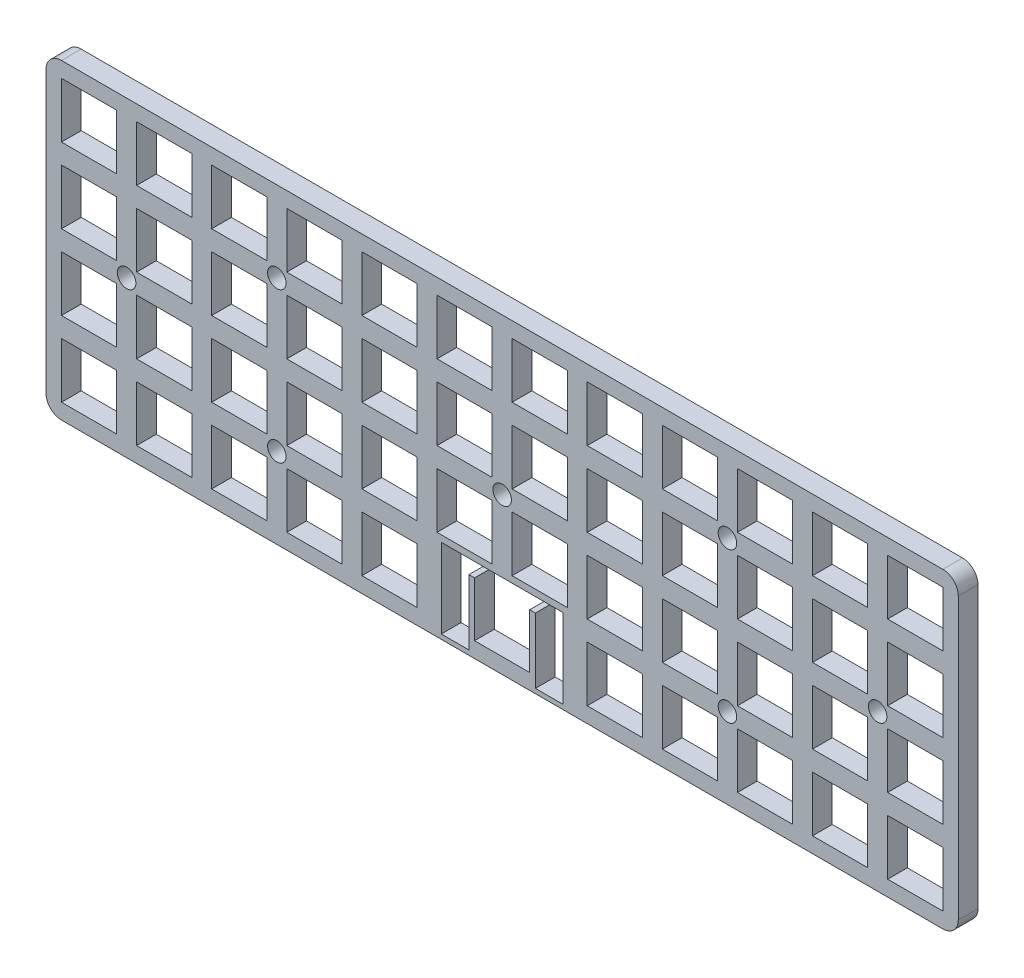
SolidWorks part; units mm, degrees
ref_plane "Alzado" through (0, 0, 0) normal (0, 0, 1) x (1, 0, 0)
ref_plane "Planta" through (0, 0, 0) normal (0, 1, 0) x (1, 0, 0)
ref_plane "Vista lateral" through (0, 0, 0) normal (1, 0, 0) x (0, 0, -1)
sketch "Reference" plane through (0, 0, 0) normal (0, 0, 1) x (1, 0, 0)
  line L0 (10.05, 76.2) -> (10.05, 83.2)
  line L1 (12.05, 85.2) -> (235.6, 85.2)
  line L2 (237.6, 83.2) -> (237.6, 12.05)
  line L3 (10.05, 12.05) -> (10.05, 76.2)
  line L4 (235.6, 10.05) -> (12.05, 10.05)
  line L5 (47.625, 85.2) -> (47.625, 87.2)
  line L6 (52.625, 87.2) -> (42.625, 87.2)
  line L7 (42.625, 87.2) -> (42.625, 85.2)
  line L8 (52.625, 87.2) -> (52.625, 85.2)
  line L9 (47.625, 87.2) -> (47.625, 89.2)
  line L10 (12.05, 69.2) -> (26.05, 69.2)
  line L11 (26.05, 83.2) -> (12.05, 83.2)
  line L12 (26.05, 69.2) -> (26.05, 83.2)
  line L13 (12.05, 83.2) -> (12.05, 69.2)
  line L14 (31.1, 69.2) -> (45.1, 69.2)
  line L15 (45.1, 83.2) -> (31.1, 83.2)
  line L16 (45.1, 69.2) -> (45.1, 83.2)
  line L17 (31.1, 83.2) -> (31.1, 69.2)
  line L18 (50.15, 69.2) -> (64.15, 69.2)
  line L19 (64.15, 83.2) -> (50.15, 83.2)
  line L20 (64.15, 69.2) -> (64.15, 83.2)
  line L21 (50.15, 83.2) -> (50.15, 69.2)
  line L22 (69.2, 69.2) -> (83.2, 69.2)
  line L23 (83.2, 83.2) -> (69.2, 83.2)
  line L24 (83.2, 69.2) -> (83.2, 83.2)
  line L25 (69.2, 83.2) -> (69.2, 69.2)
  line L26 (88.25, 69.2) -> (102.25, 69.2)
  line L27 (102.25, 83.2) -> (88.25, 83.2)
  line L28 (102.25, 69.2) -> (102.25, 83.2)
  line L29 (88.25, 83.2) -> (88.25, 69.2)
  line L30 (107.3, 69.2) -> (121.3, 69.2)
  line L31 (121.3, 83.2) -> (107.3, 83.2)
  line L32 (121.3, 69.2) -> (121.3, 83.2)
  line L33 (107.3, 83.2) -> (107.3, 69.2)
  line L34 (126.35, 69.2) -> (140.35, 69.2)
  line L35 (140.35, 83.2) -> (126.35, 83.2)
  line L36 (140.35, 69.2) -> (140.35, 83.2)
  line L37 (126.35, 83.2) -> (126.35, 69.2)
  line L38 (145.4, 69.2) -> (159.4, 69.2)
  line L39 (159.4, 83.2) -> (145.4, 83.2)
  line L40 (159.4, 69.2) -> (159.4, 83.2)
  line L41 (145.4, 83.2) -> (145.4, 69.2)
  line L42 (164.45, 69.2) -> (178.45, 69.2)
  line L43 (178.45, 83.2) -> (164.45, 83.2)
  line L44 (178.45, 69.2) -> (178.45, 83.2)
  line L45 (164.45, 83.2) -> (164.45, 69.2)
  line L46 (183.5, 69.2) -> (197.5, 69.2)
  line L47 (197.5, 83.2) -> (183.5, 83.2)
  line L48 (197.5, 69.2) -> (197.5, 83.2)
  line L49 (183.5, 83.2) -> (183.5, 69.2)
  line L50 (202.55, 69.2) -> (216.55, 69.2)
  line L51 (216.55, 83.2) -> (202.55, 83.2)
  line L52 (216.55, 69.2) -> (216.55, 83.2)
  line L53 (202.55, 83.2) -> (202.55, 69.2)
  line L54 (221.6, 69.2) -> (235.6, 69.2)
  line L55 (235.6, 83.2) -> (221.6, 83.2)
  line L56 (235.6, 69.2) -> (235.6, 83.2)
  line L57 (221.6, 83.2) -> (221.6, 69.2)
  line L58 (12.05, 50.15) -> (26.05, 50.15)
  line L59 (26.05, 64.15) -> (12.05, 64.15)
  line L60 (26.05, 50.15) -> (26.05, 64.15)
  line L61 (12.05, 64.15) -> (12.05, 50.15)
  line L62 (31.1, 50.15) -> (45.1, 50.15)
  line L63 (45.1, 64.15) -> (31.1, 64.15)
  line L64 (45.1, 50.15) -> (45.1, 64.15)
  line L65 (31.1, 64.15) -> (31.1, 50.15)
  line L66 (50.15, 50.15) -> (64.15, 50.15)
  line L67 (64.15, 64.15) -> (50.15, 64.15)
  line L68 (64.15, 50.15) -> (64.15, 64.15)
  line L69 (50.15, 64.15) -> (50.15, 50.15)
  line L70 (69.2, 50.15) -> (83.2, 50.15)
  line L71 (83.2, 64.15) -> (69.2, 64.15)
  line L72 (83.2, 50.15) -> (83.2, 64.15)
  line L73 (69.2, 64.15) -> (69.2, 50.15)
  line L74 (88.25, 50.15) -> (102.25, 50.15)
  line L75 (102.25, 64.15) -> (88.25, 64.15)
  line L76 (102.25, 50.15) -> (102.25, 64.15)
  line L77 (88.25, 64.15) -> (88.25, 50.15)
  line L78 (107.3, 50.15) -> (121.3, 50.15)
  line L79 (121.3, 64.15) -> (107.3, 64.15)
  line L80 (121.3, 50.15) -> (121.3, 64.15)
  line L81 (107.3, 64.15) -> (107.3, 50.15)
  line L82 (126.35, 50.15) -> (140.35, 50.15)
  line L83 (140.35, 64.15) -> (126.35, 64.15)
  line L84 (140.35, 50.15) -> (140.35, 64.15)
  line L85 (126.35, 64.15) -> (126.35, 50.15)
  line L86 (145.4, 50.15) -> (159.4, 50.15)
  line L87 (159.4, 64.15) -> (145.4, 64.15)
  line L88 (159.4, 50.15) -> (159.4, 64.15)
  line L89 (145.4, 64.15) -> (145.4, 50.15)
  line L90 (164.45, 50.15) -> (178.45, 50.15)
  line L91 (178.45, 64.15) -> (164.45, 64.15)
  line L92 (178.45, 50.15) -> (178.45, 64.15)
  line L93 (164.45, 64.15) -> (164.45, 50.15)
  line L94 (183.5, 50.15) -> (197.5, 50.15)
  line L95 (197.5, 64.15) -> (183.5, 64.15)
  line L96 (197.5, 50.15) -> (197.5, 64.15)
  line L97 (183.5, 64.15) -> (183.5, 50.15)
  line L98 (202.55, 50.15) -> (216.55, 50.15)
  line L99 (216.55, 64.15) -> (202.55, 64.15)
  line L100 (216.55, 50.15) -> (216.55, 64.15)
  line L101 (202.55, 64.15) -> (202.55, 50.15)
  line L102 (221.6, 50.15) -> (235.6, 50.15)
  line L103 (235.6, 64.15) -> (221.6, 64.15)
  line L104 (235.6, 50.15) -> (235.6, 64.15)
  line L105 (221.6, 64.15) -> (221.6, 50.15)
  line L106 (12.05, 31.1) -> (26.05, 31.1)
  line L107 (26.05, 45.1) -> (12.05, 45.1)
  line L108 (26.05, 31.1) -> (26.05, 45.1)
  line L109 (12.05, 45.1) -> (12.05, 31.1)
  line L110 (31.1, 31.1) -> (45.1, 31.1)
  line L111 (45.1, 45.1) -> (31.1, 45.1)
  line L112 (45.1, 31.1) -> (45.1, 45.1)
  line L113 (31.1, 45.1) -> (31.1, 31.1)
  line L114 (50.15, 31.1) -> (64.15, 31.1)
  line L115 (64.15, 45.1) -> (50.15, 45.1)
  line L116 (64.15, 31.1) -> (64.15, 45.1)
  line L117 (50.15, 45.1) -> (50.15, 31.1)
  line L118 (69.2, 31.1) -> (83.2, 31.1)
  line L119 (83.2, 45.1) -> (69.2, 45.1)
  line L120 (83.2, 31.1) -> (83.2, 45.1)
  line L121 (69.2, 45.1) -> (69.2, 31.1)
  line L122 (88.25, 31.1) -> (102.25, 31.1)
  line L123 (102.25, 45.1) -> (88.25, 45.1)
  line L124 (102.25, 31.1) -> (102.25, 45.1)
  line L125 (88.25, 45.1) -> (88.25, 31.1)
  line L126 (107.3, 31.1) -> (121.3, 31.1)
  line L127 (121.3, 45.1) -> (107.3, 45.1)
  line L128 (121.3, 31.1) -> (121.3, 45.1)
  line L129 (107.3, 45.1) -> (107.3, 31.1)
  line L130 (126.35, 31.1) -> (140.35, 31.1)
  line L131 (140.35, 45.1) -> (126.35, 45.1)
  line L132 (140.35, 31.1) -> (140.35, 45.1)
  line L133 (126.35, 45.1) -> (126.35, 31.1)
  line L134 (145.4, 31.1) -> (159.4, 31.1)
  line L135 (159.4, 45.1) -> (145.4, 45.1)
  line L136 (159.4, 31.1) -> (159.4, 45.1)
  line L137 (145.4, 45.1) -> (145.4, 31.1)
  line L138 (164.45, 31.1) -> (178.45, 31.1)
  line L139 (178.45, 45.1) -> (164.45, 45.1)
  line L140 (178.45, 31.1) -> (178.45, 45.1)
  line L141 (164.45, 45.1) -> (164.45, 31.1)
  line L142 (183.5, 31.1) -> (197.5, 31.1)
  line L143 (197.5, 45.1) -> (183.5, 45.1)
  line L144 (197.5, 31.1) -> (197.5, 45.1)
  line L145 (183.5, 45.1) -> (183.5, 31.1)
  line L146 (202.55, 31.1) -> (216.55, 31.1)
  line L147 (216.55, 45.1) -> (202.55, 45.1)
  line L148 (216.55, 31.1) -> (216.55, 45.1)
  line L149 (202.55, 45.1) -> (202.55, 31.1)
  line L150 (221.6, 31.1) -> (235.6, 31.1)
  line L151 (235.6, 45.1) -> (221.6, 45.1)
  line L152 (235.6, 31.1) -> (235.6, 45.1)
  line L153 (221.6, 45.1) -> (221.6, 31.1)
  line L154 (12.05, 12.05) -> (26.05, 12.05)
  line L155 (26.05, 26.05) -> (12.05, 26.05)
  line L156 (26.05, 12.05) -> (26.05, 26.05)
  line L157 (12.05, 26.05) -> (12.05, 12.05)
  line L158 (31.1, 12.05) -> (45.1, 12.05)
  line L159 (45.1, 26.05) -> (31.1, 26.05)
  line L160 (45.1, 12.05) -> (45.1, 26.05)
  line L161 (31.1, 26.05) -> (31.1, 12.05)
  line L162 (50.15, 12.05) -> (64.15, 12.05)
  line L163 (64.15, 26.05) -> (50.15, 26.05)
  line L164 (64.15, 12.05) -> (64.15, 26.05)
  line L165 (50.15, 26.05) -> (50.15, 12.05)
  line L166 (69.2, 12.05) -> (83.2, 12.05)
  line L167 (83.2, 26.05) -> (69.2, 26.05)
  line L168 (83.2, 12.05) -> (83.2, 26.05)
  line L169 (69.2, 26.05) -> (69.2, 12.05)
  line L170 (88.25, 12.05) -> (102.25, 12.05)
  line L171 (102.25, 26.05) -> (88.25, 26.05)
  line L172 (102.25, 12.05) -> (102.25, 26.05)
  line L173 (88.25, 26.05) -> (88.25, 12.05)
  line L174 (145.4, 12.05) -> (159.4, 12.05)
  line L175 (159.4, 26.05) -> (145.4, 26.05)
  line L176 (159.4, 12.05) -> (159.4, 26.05)
  line L177 (145.4, 26.05) -> (145.4, 12.05)
  line L178 (164.45, 12.05) -> (178.45, 12.05)
  line L179 (178.45, 26.05) -> (164.45, 26.05)
  line L180 (178.45, 12.05) -> (178.45, 26.05)
  line L181 (164.45, 26.05) -> (164.45, 12.05)
  line L182 (183.5, 12.05) -> (197.5, 12.05)
  line L183 (197.5, 26.05) -> (183.5, 26.05)
  line L184 (197.5, 12.05) -> (197.5, 26.05)
  line L185 (183.5, 26.05) -> (183.5, 12.05)
  line L186 (202.55, 12.05) -> (216.55, 12.05)
  line L187 (216.55, 26.05) -> (202.55, 26.05)
  line L188 (216.55, 12.05) -> (216.55, 26.05)
  line L189 (202.55, 26.05) -> (202.55, 12.05)
  line L190 (221.6, 12.05) -> (235.6, 12.05)
  line L191 (235.6, 26.05) -> (221.6, 26.05)
  line L192 (235.6, 12.05) -> (235.6, 26.05)
  line L193 (221.6, 26.05) -> (221.6, 12.05)
  line L194 (121.3, 31.1) -> (126.35, 31.1)
  line L195 (130.825, 26.05) -> (116.825, 26.05)
  line L196 (116.825, 12.05) -> (130.825, 12.05)
  line L197 (116.825, 26.05) -> (116.825, 12.05)
  line L198 (130.825, 12.05) -> (130.825, 26.05)
  line L199 (139.263, 27.05) -> (132.263, 27.05)
  line L200 (132.263, 12.05) -> (139.263, 12.05)
  line L201 (132.263, 27.05) -> (132.263, 12.05)
  line L202 (139.263, 12.05) -> (139.263, 27.05)
  line L203 (115.387, 27.05) -> (108.387, 27.05)
  line L204 (108.387, 12.05) -> (115.387, 12.05)
  line L205 (108.387, 27.05) -> (108.387, 12.05)
  line L206 (115.387, 12.05) -> (115.387, 27.05)
  line L207 (139.263, 28.05) -> (132.263, 28.05)
  line L208 (115.387, 28.05) -> (108.387, 28.05)
  line L209 (115.387, 28.05) -> (115.387, 27.05)
  line L210 (108.387, 28.05) -> (108.387, 27.05)
  line L211 (132.263, 28.05) -> (132.263, 27.05)
  line L212 (139.263, 28.05) -> (139.263, 27.05)
  line L213 (139.263, 29.45) -> (135.763, 29.45)
  line L214 (135.763, 29.45) -> (132.263, 29.45)
  line L215 (132.263, 9.3) -> (139.263, 9.3)
  line L216 (115.387, 29.45) -> (111.887, 29.45)
  line L217 (111.887, 29.45) -> (108.387, 29.45)
  line L218 (108.387, 9.3) -> (115.387, 9.3)
  line L219 (132.263, 29.45) -> (115.387, 29.45)
  line L220 (115.387, 25.85) -> (116.825, 25.85)
  line L221 (130.825, 25.85) -> (132.263, 25.85)
  line L222 (132.263, 9.3) -> (132.263, 12.05)
  line L223 (139.263, 9.3) -> (139.263, 12.05)
  line L224 (115.387, 9.3) -> (115.387, 12.05)
  line L225 (108.387, 9.3) -> (108.387, 12.05)
  line L226 (108.387, 29.45) -> (108.387, 28.05)
  line L227 (139.263, 29.45) -> (139.263, 28.05)
  circle A0 centre (19.05, 76.2) radius 2
  arc A1 (12.05, 85.2) -> (10.05, 83.2) centre (12.05, 83.2) ccw
  arc A2 (237.6, 83.2) -> (235.6, 85.2) centre (235.6, 83.2) ccw
  arc A3 (235.6, 10.05) -> (237.6, 12.05) centre (235.6, 12.05) ccw
  arc A4 (10.05, 12.05) -> (12.05, 10.05) centre (12.05, 12.05) ccw
  circle A5 centre (111.887, 27.305) radius 2
  circle A6 centre (111.887, 12.065) radius 1.524
  circle A7 centre (135.763, 12.065) radius 1.524
  circle A8 centre (135.763, 27.305) radius 2
  circle A9 centre (38.1, 76.2) radius 2
  circle A10 centre (57.15, 76.2) radius 2
  circle A11 centre (76.2, 76.2) radius 2
  circle A12 centre (95.25, 76.2) radius 2
  circle A13 centre (114.3, 76.2) radius 2
  circle A14 centre (133.35, 76.2) radius 2
  circle A15 centre (152.4, 76.2) radius 2
  circle A16 centre (171.45, 76.2) radius 2
  circle A17 centre (190.5, 76.2) radius 2
  circle A18 centre (209.55, 76.2) radius 2
  circle A19 centre (228.6, 76.2) radius 2
  circle A20 centre (19.05, 57.15) radius 2
  circle A21 centre (38.1, 57.15) radius 2
  circle A22 centre (57.15, 57.15) radius 2
  circle A23 centre (76.2, 57.15) radius 2
  circle A24 centre (95.25, 57.15) radius 2
  circle A25 centre (114.3, 57.15) radius 2
  circle A26 centre (133.35, 57.15) radius 2
  circle A27 centre (152.4, 57.15) radius 2
  circle A28 centre (171.45, 57.15) radius 2
  circle A29 centre (190.5, 57.15) radius 2
  circle A30 centre (209.55, 57.15) radius 2
  circle A31 centre (228.6, 57.15) radius 2
  circle A32 centre (19.05, 38.1) radius 2
  circle A33 centre (38.1, 38.1) radius 2
  circle A34 centre (57.15, 38.1) radius 2
  circle A35 centre (76.2, 38.1) radius 2
  circle A36 centre (95.25, 38.1) radius 2
  circle A37 centre (114.3, 38.1) radius 2
  circle A38 centre (133.35, 38.1) radius 2
  circle A39 centre (152.4, 38.1) radius 2
  circle A40 centre (171.45, 38.1) radius 2
  circle A41 centre (190.5, 38.1) radius 2
  circle A42 centre (209.55, 38.1) radius 2
  circle A43 centre (228.6, 38.1) radius 2
  circle A44 centre (19.05, 19.05) radius 2
  circle A45 centre (38.1, 19.05) radius 2
  circle A46 centre (57.15, 19.05) radius 2
  circle A47 centre (76.2, 19.05) radius 2
  circle A48 centre (95.25, 19.05) radius 2
  circle A49 centre (152.4, 19.05) radius 2
  circle A50 centre (171.45, 19.05) radius 2
  circle A51 centre (190.5, 19.05) radius 2
  circle A52 centre (209.55, 19.05) radius 2
  circle A53 centre (228.6, 19.05) radius 2
  circle A54 centre (28.575, 47.625) radius 1.35
  circle A55 centre (66.675, 66.675) radius 1.35
  circle A56 centre (66.675, 28.575) radius 1.35
  circle A57 centre (123.825, 47.625) radius 1.35
  circle A58 centre (180.975, 66.675) radius 1.35
  circle A59 centre (180.975, 28.575) radius 1.35
  circle A60 centre (219.075, 47.625) radius 1.35
  circle A61 centre (123.825, 19.05) radius 2
sketch "Croquis3" plane through (0, 0, 0) normal (0, 0, 1) x (1, 0, 0)
  line L0 (12.05, 85.2) -> (235.6, 85.2) construction
  line L1 (12.05, 10.05) -> (235.6, 10.05) construction
  line L2 (10.05, 12.05) -> (10.05, 83.2) construction
  line L3 (12.05, 85.2) -> (42.625, 85.2) construction
  line L4 (237.6, 12.05) -> (237.6, 83.2) construction
  line L5 (10.05, 12.05) -> (10.05, 76.2) construction
  line L6 (237.6, 83.2) -> (237.6, 12.05) construction
  line L7 (235.6, 10.05) -> (12.05, 10.05) construction
  line L8 (42.625, 85.2) -> (42.625, 87.2) construction
  line L9 (42.625, 87.2) -> (52.625, 87.2) construction
  line L10 (52.625, 87.2) -> (52.625, 85.2) construction
  line L11 (52.625, 85.2) -> (235.6, 85.2) construction
  line L12 (31.1, 69.2) -> (31.1, 83.2)
  line L13 (12.05, 69.2) -> (26.05, 69.2)
  line L14 (12.05, 69.2) -> (12.05, 83.2)
  line L15 (12.05, 83.2) -> (26.05, 83.2)
  line L16 (26.05, 69.2) -> (26.05, 83.2)
  line L17 (31.1, 69.2) -> (45.1, 69.2)
  line L18 (45.1, 69.2) -> (45.1, 83.2)
  line L19 (31.1, 83.2) -> (45.1, 83.2)
  line L20 (50.15, 69.2) -> (50.15, 83.2)
  line L21 (50.15, 69.2) -> (64.15, 69.2)
  line L22 (64.15, 69.2) -> (64.15, 83.2)
  line L23 (50.15, 83.2) -> (64.15, 83.2)
  line L24 (69.2, 69.2) -> (69.2, 83.2)
  line L25 (69.2, 69.2) -> (83.2, 69.2)
  line L26 (83.2, 69.2) -> (83.2, 83.2)
  line L27 (69.2, 83.2) -> (83.2, 83.2)
  line L28 (88.25, 69.2) -> (88.25, 83.2)
  line L29 (88.25, 69.2) -> (102.25, 69.2)
  line L30 (102.25, 69.2) -> (102.25, 83.2)
  line L31 (88.25, 83.2) -> (102.25, 83.2)
  line L32 (107.3, 69.2) -> (107.3, 83.2)
  line L33 (107.3, 69.2) -> (121.3, 69.2)
  line L34 (121.3, 69.2) -> (121.3, 83.2)
  line L35 (107.3, 83.2) -> (121.3, 83.2)
  line L36 (126.35, 69.2) -> (126.35, 83.2)
  line L37 (126.35, 69.2) -> (140.35, 69.2)
  line L38 (140.35, 69.2) -> (140.35, 83.2)
  line L39 (126.35, 83.2) -> (140.35, 83.2)
  line L40 (145.4, 69.2) -> (145.4, 83.2)
  line L41 (145.4, 69.2) -> (159.4, 69.2)
  line L42 (159.4, 69.2) -> (159.4, 83.2)
  line L43 (145.4, 83.2) -> (159.4, 83.2)
  line L44 (164.45, 69.2) -> (164.45, 83.2)
  line L45 (164.45, 69.2) -> (178.45, 69.2)
  line L46 (178.45, 69.2) -> (178.45, 83.2)
  line L47 (164.45, 83.2) -> (178.45, 83.2)
  line L48 (183.5, 69.2) -> (183.5, 83.2)
  line L49 (183.5, 69.2) -> (197.5, 69.2)
  line L50 (197.5, 69.2) -> (197.5, 83.2)
  line L51 (183.5, 83.2) -> (197.5, 83.2)
  line L52 (202.55, 69.2) -> (202.55, 83.2)
  line L53 (202.55, 69.2) -> (216.55, 69.2)
  line L54 (216.55, 69.2) -> (216.55, 83.2)
  line L55 (202.55, 83.2) -> (216.55, 83.2)
  line L56 (221.6, 69.2) -> (221.6, 83.2)
  line L57 (221.6, 69.2) -> (235.6, 69.2)
  line L58 (235.6, 69.2) -> (235.6, 83.2)
  line L59 (221.6, 83.2) -> (235.6, 83.2)
  line L60 (31.1, 50.15) -> (31.1, 64.15)
  line L61 (31.1, 50.15) -> (45.1, 50.15)
  line L62 (45.1, 50.15) -> (45.1, 64.15)
  line L63 (31.1, 64.15) -> (45.1, 64.15)
  line L64 (50.15, 50.15) -> (50.15, 64.15)
  line L65 (50.15, 50.15) -> (64.15, 50.15)
  line L66 (64.15, 50.15) -> (64.15, 64.15)
  line L67 (50.15, 64.15) -> (64.15, 64.15)
  line L68 (69.2, 50.15) -> (69.2, 64.15)
  line L69 (69.2, 50.15) -> (83.2, 50.15)
  line L70 (83.2, 50.15) -> (83.2, 64.15)
  line L71 (69.2, 64.15) -> (83.2, 64.15)
  line L72 (88.25, 50.15) -> (88.25, 64.15)
  line L73 (88.25, 50.15) -> (102.25, 50.15)
  line L74 (102.25, 50.15) -> (102.25, 64.15)
  line L75 (88.25, 64.15) -> (102.25, 64.15)
  line L76 (107.3, 50.15) -> (107.3, 64.15)
  line L77 (107.3, 50.15) -> (121.3, 50.15)
  line L78 (121.3, 50.15) -> (121.3, 64.15)
  line L79 (107.3, 64.15) -> (121.3, 64.15)
  line L80 (126.35, 50.15) -> (126.35, 64.15)
  line L81 (126.35, 50.15) -> (140.35, 50.15)
  line L82 (140.35, 50.15) -> (140.35, 64.15)
  line L83 (126.35, 64.15) -> (140.35, 64.15)
  line L84 (145.4, 50.15) -> (145.4, 64.15)
  line L85 (145.4, 50.15) -> (159.4, 50.15)
  line L86 (159.4, 50.15) -> (159.4, 64.15)
  line L87 (145.4, 64.15) -> (159.4, 64.15)
  line L88 (164.45, 50.15) -> (164.45, 64.15)
  line L89 (164.45, 50.15) -> (178.45, 50.15)
  line L90 (178.45, 50.15) -> (178.45, 64.15)
  line L91 (164.45, 64.15) -> (178.45, 64.15)
  line L92 (183.5, 50.15) -> (183.5, 64.15)
  line L93 (183.5, 50.15) -> (197.5, 50.15)
  line L94 (197.5, 50.15) -> (197.5, 64.15)
  line L95 (183.5, 64.15) -> (197.5, 64.15)
  line L96 (202.55, 50.15) -> (202.55, 64.15)
  line L97 (202.55, 50.15) -> (216.55, 50.15)
  line L98 (216.55, 50.15) -> (216.55, 64.15)
  line L99 (202.55, 64.15) -> (216.55, 64.15)
  line L100 (221.6, 50.15) -> (221.6, 64.15)
  line L101 (221.6, 50.15) -> (235.6, 50.15)
  line L102 (235.6, 50.15) -> (235.6, 64.15)
  line L103 (221.6, 64.15) -> (235.6, 64.15)
  line L104 (31.1, 31.1) -> (31.1, 45.1)
  line L105 (31.1, 31.1) -> (45.1, 31.1)
  line L106 (45.1, 31.1) -> (45.1, 45.1)
  line L107 (31.1, 45.1) -> (45.1, 45.1)
  line L108 (50.15, 31.1) -> (50.15, 45.1)
  line L109 (50.15, 31.1) -> (64.15, 31.1)
  line L110 (64.15, 31.1) -> (64.15, 45.1)
  line L111 (50.15, 45.1) -> (64.15, 45.1)
  line L112 (69.2, 31.1) -> (69.2, 45.1)
  line L113 (69.2, 31.1) -> (83.2, 31.1)
  line L114 (83.2, 31.1) -> (83.2, 45.1)
  line L115 (69.2, 45.1) -> (83.2, 45.1)
  line L116 (88.25, 31.1) -> (88.25, 45.1)
  line L117 (88.25, 31.1) -> (102.25, 31.1)
  line L118 (102.25, 31.1) -> (102.25, 45.1)
  line L119 (88.25, 45.1) -> (102.25, 45.1)
  line L120 (107.3, 31.1) -> (107.3, 45.1)
  line L121 (107.3, 31.1) -> (121.3, 31.1)
  line L122 (121.3, 31.1) -> (121.3, 45.1)
  line L123 (107.3, 45.1) -> (121.3, 45.1)
  line L124 (126.35, 31.1) -> (126.35, 45.1)
  line L125 (126.35, 31.1) -> (140.35, 31.1)
  line L126 (140.35, 31.1) -> (140.35, 45.1)
  line L127 (126.35, 45.1) -> (140.35, 45.1)
  line L128 (145.4, 31.1) -> (145.4, 45.1)
  line L129 (145.4, 31.1) -> (159.4, 31.1)
  line L130 (159.4, 31.1) -> (159.4, 45.1)
  line L131 (145.4, 45.1) -> (159.4, 45.1)
  line L132 (164.45, 31.1) -> (164.45, 45.1)
  line L133 (164.45, 31.1) -> (178.45, 31.1)
  line L134 (178.45, 31.1) -> (178.45, 45.1)
  line L135 (164.45, 45.1) -> (178.45, 45.1)
  line L136 (183.5, 31.1) -> (183.5, 45.1)
  line L137 (183.5, 31.1) -> (197.5, 31.1)
  line L138 (197.5, 31.1) -> (197.5, 45.1)
  line L139 (183.5, 45.1) -> (197.5, 45.1)
  line L140 (202.55, 31.1) -> (202.55, 45.1)
  line L141 (202.55, 31.1) -> (216.55, 31.1)
  line L142 (216.55, 31.1) -> (216.55, 45.1)
  line L143 (202.55, 45.1) -> (216.55, 45.1)
  line L144 (221.6, 31.1) -> (221.6, 45.1)
  line L145 (221.6, 31.1) -> (235.6, 31.1)
  line L146 (235.6, 31.1) -> (235.6, 45.1)
  line L147 (221.6, 45.1) -> (235.6, 45.1)
  line L148 (31.1, 12.05) -> (31.1, 26.05)
  line L149 (31.1, 12.05) -> (45.1, 12.05)
  line L150 (45.1, 12.05) -> (45.1, 26.05)
  line L151 (31.1, 26.05) -> (45.1, 26.05)
  line L152 (50.15, 12.05) -> (50.15, 26.05)
  line L153 (50.15, 12.05) -> (64.15, 12.05)
  line L154 (64.15, 12.05) -> (64.15, 26.05)
  line L155 (50.15, 26.05) -> (64.15, 26.05)
  line L156 (69.2, 12.05) -> (69.2, 26.05)
  line L157 (69.2, 12.05) -> (83.2, 12.05)
  line L158 (83.2, 12.05) -> (83.2, 26.05)
  line L159 (69.2, 26.05) -> (83.2, 26.05)
  line L160 (88.25, 12.05) -> (88.25, 26.05)
  line L161 (88.25, 12.05) -> (102.25, 12.05)
  line L162 (102.25, 12.05) -> (102.25, 26.05)
  line L163 (88.25, 26.05) -> (102.25, 26.05)
  line L172 (145.4, 12.05) -> (145.4, 26.05)
  line L173 (145.4, 12.05) -> (159.4, 12.05)
  line L174 (159.4, 12.05) -> (159.4, 26.05)
  line L175 (145.4, 26.05) -> (159.4, 26.05)
  line L176 (164.45, 12.05) -> (164.45, 26.05)
  line L177 (164.45, 12.05) -> (178.45, 12.05)
  line L178 (178.45, 12.05) -> (178.45, 26.05)
  line L179 (164.45, 26.05) -> (178.45, 26.05)
  line L180 (183.5, 12.05) -> (183.5, 26.05)
  line L181 (183.5, 12.05) -> (197.5, 12.05)
  line L182 (197.5, 12.05) -> (197.5, 26.05)
  line L183 (183.5, 26.05) -> (197.5, 26.05)
  line L184 (202.55, 12.05) -> (202.55, 26.05)
  line L185 (202.55, 12.05) -> (216.55, 12.05)
  line L186 (216.55, 12.05) -> (216.55, 26.05)
  line L187 (202.55, 26.05) -> (216.55, 26.05)
  line L188 (221.6, 12.05) -> (221.6, 26.05)
  line L189 (221.6, 12.05) -> (235.6, 12.05)
  line L190 (235.6, 12.05) -> (235.6, 26.05)
  line L191 (221.6, 26.05) -> (235.6, 26.05)
  line L192 (12.05, 50.15) -> (12.05, 64.15)
  line L193 (12.05, 50.15) -> (26.05, 50.15)
  line L194 (26.05, 50.15) -> (26.05, 64.15)
  line L195 (12.05, 64.15) -> (26.05, 64.15)
  line L196 (12.05, 31.1) -> (12.05, 45.1)
  line L197 (12.05, 31.1) -> (26.05, 31.1)
  line L198 (26.05, 31.1) -> (26.05, 45.1)
  line L199 (12.05, 45.1) -> (26.05, 45.1)
  line L200 (12.05, 12.05) -> (12.05, 26.05)
  line L201 (12.05, 12.05) -> (26.05, 12.05)
  line L202 (26.05, 12.05) -> (26.05, 26.05)
  line L203 (12.05, 26.05) -> (26.05, 26.05)
  line L204 (12.05, 69.2) -> (31.1, 69.2) construction
  line L205 (12.05, 69.2) -> (12.05, 50.15) construction
  line L206 (45.1, 50.15) -> (45.1, 64.15) construction
  line L207 (107.3, 12.05) -> (107.3, 26.05) [skipped]
  line L208 (107.3, 26.05) -> (121.3, 26.05) [skipped]
  line L209 (121.3, 12.05) -> (121.3, 26.05) [skipped]
  line L210 (107.3, 12.05) -> (121.3, 12.05) [skipped]
  line L211 (126.35, 12.05) -> (126.35, 26.05) [skipped]
  line L212 (126.35, 26.05) -> (140.35, 26.05) [skipped]
  line L213 (140.35, 12.05) -> (140.35, 26.05) [skipped]
  line L214 (126.35, 12.05) -> (140.35, 12.05) [skipped]
  line L216 (116.825, 12.05) -> (130.825, 12.05)
  line L217 (116.825, 12.05) -> (116.825, 26.05)
  line L218 (116.825, 26.05) -> (130.825, 26.05)
  line L219 (130.825, 12.05) -> (130.825, 26.05)
  line L224 (239.525, 12.05) -> (239.525, 83.2)
  line L225 (12.05, 8.125) -> (235.6, 8.125)
  line L226 (8.125, 12.05) -> (8.125, 83.2)
  line L227 (42.625, 87.125) -> (52.625, 87.125)
  line L228 (12.05, 87.125) -> (235.6, 87.125)
  line L229 (12.05, 87.125) -> (40.7, 87.125) construction
  line L230 (40.7, 87.125) -> (40.7, 89.125) construction
  line L231 (40.7, 89.125) -> (54.55, 89.125) construction
  line L232 (54.55, 89.125) -> (54.55, 87.125) construction
  line L233 (54.55, 87.125) -> (235.6, 87.125) construction
  arc A0 (235.6, 10.05) -> (237.6, 12.05) centre (235.6, 12.05) ccw construction
  arc A1 (235.6, 85.2) -> (237.6, 83.2) centre (235.6, 83.2) cw construction
  arc A2 (10.05, 83.2) -> (12.05, 85.2) centre (12.05, 83.2) cw construction
  arc A3 (12.05, 10.05) -> (10.05, 12.05) centre (12.05, 12.05) cw construction
  arc A5 (235.6, 87.125) -> (239.525, 83.2) centre (235.6, 83.2) cw
  arc A7 (235.6, 8.125) -> (239.525, 12.05) centre (235.6, 12.05) ccw
  circle A8 centre (66.675, 66.675) radius 2.35
  circle A9 centre (123.825, 47.625) radius 2.35
  circle A10 centre (180.975, 66.675) radius 2.35
  circle A11 centre (180.975, 28.575) radius 2.35
  circle A12 centre (28.575, 47.625) radius 2.35
  circle A13 centre (66.675, 28.575) radius 2.35
  circle A14 centre (219.075, 47.625) radius 2.35
  arc A15 (12.05, 8.125) -> (8.125, 12.05) centre (12.05, 12.05) cw
  arc A16 (8.125, 83.2) -> (12.05, 87.125) centre (12.05, 83.2) cw
  dimension "D1" = 2
  dimension "D6" = 4.7
  dimension "D4" = 19.05
  dimension "D5" = 19.05
  dimension "D7" = 1.925
  dimension "D2" = 12
  dimension "D3" = 4
extrude "MainPlate" add sketch "Croquis3" along normal blind 5 contours A16 L226 A15 L225 A7 L224 A5 L228 L227 A14 A13 A12 A11 A10 A9 A8 L219 L216 L217 L218 L16 L13 L14 L15 L12 L19 L18 L17 L20 L23 L22 L21 L24 L27 L26 L25 L28
sketch "Croquis4" [suppressed] plane through (0, 0, 1.5) normal (0, 0, 1) x (1, 0, 0)
  line L1 (108.387, 12.05) -> (115.387, 12.05)
  line L2 (108.387, 12.05) -> (108.387, 27.05)
  line L3 (108.387, 27.05) -> (115.387, 27.05)
  line L4 (115.387, 12.05) -> (115.387, 27.05)
  line L5 (132.263, 12.05) -> (139.263, 12.05)
  line L6 (132.263, 12.05) -> (132.263, 27.05)
  line L7 (132.263, 27.05) -> (139.263, 27.05)
  line L8 (139.263, 12.05) -> (139.263, 27.05)
extrude "1.5mm cutout" [suppressed] cut sketch "Croquis4" against normal through all
sketch "Croquis6" [suppressed] plane through (0, 0, 3) normal (0, 0, 1) x (1, 0, 0)
  line L1 (108.387, 12.05) -> (115.387, 12.05)
  line L2 (108.387, 12.05) -> (108.387, 28.05)
  line L3 (108.387, 28.05) -> (115.387, 28.05)
  line L4 (115.387, 12.05) -> (115.387, 28.05)
  line L5 (132.263, 12.05) -> (139.263, 12.05)
  line L6 (132.263, 12.05) -> (132.263, 28.05)
  line L7 (132.263, 28.05) -> (139.263, 28.05)
  line L8 (139.263, 12.05) -> (139.263, 28.05)
extrude "3mm cutout" [suppressed] cut sketch "Croquis6" against normal through all
sketch "Croquis7" plane through (0, 0, 5) normal (0, 0, 1) x (1, 0, 0)
  line L0 (108.387, 9.3) -> (115.387, 9.3)
  line L2 (108.387, 9.3) -> (108.387, 29.45)
  line L3 (108.387, 29.45) -> (139.263, 29.45)
  line L5 (115.387, 9.3) -> (115.387, 25.85)
  line L6 (115.387, 25.85) -> (132.263, 25.85)
  line L7 (132.263, 25.85) -> (132.263, 9.3)
  line L8 (132.263, 9.3) -> (139.263, 9.3)
  line L9 (139.263, 9.3) -> (139.263, 29.45)
extrude "5mm cutout" cut sketch "Croquis7" against normal through all
equation "\"thickness\"= 5"
equation "\"D1@MainPlate\" = \"thickness\""
